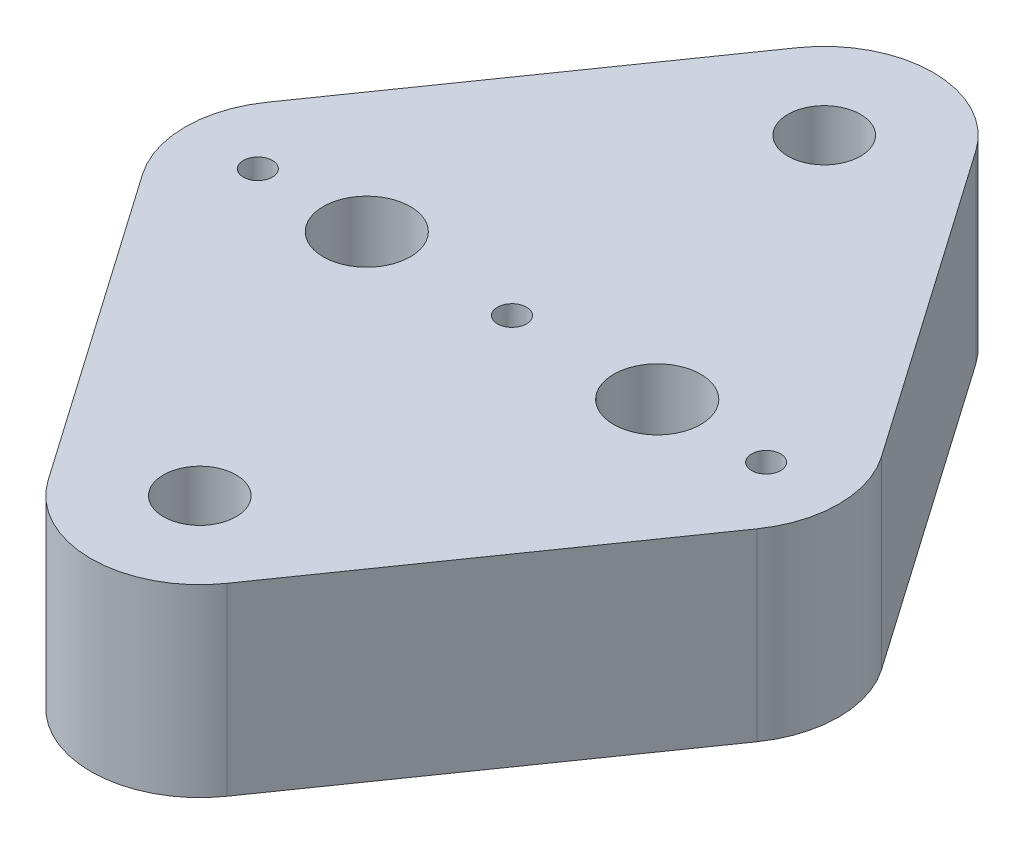
SolidWorks part; units mm, degrees
ref_plane "Front Plane" through (0, 0, 0) normal (0, 0, 1) x (1, 0, 0)
ref_plane "Top Plane" through (0, 0, 0) normal (0, 1, 0) x (1, 0, 0)
ref_plane "Right Plane" through (0, 0, 0) normal (1, 0, 0) x (0, 0, -1)
other "Default"
sketch "Sketch1" plane through (0, 0, 0) normal (0, 1, 0) x (1, 0, 0)
  line L0 (0, -21.5) -> (0, 21.5) construction
  line L1 (10, 0) -> (-10, 0) construction
  line L2 (-21.151, 4.2914) -> (-6.151, 25.7914)
  line L3 (6.151, 25.7914) -> (21.151, 4.2914)
  line L4 (21.151, -4.2914) -> (6.151, -25.7914)
  line L5 (-6.151, -25.7914) -> (-21.151, -4.2914)
  line L6 (-15, 0) -> (-10, 0) construction
  line L7 (10, 0) -> (15, 0) construction
  circle A0 centre (0, 21.5) radius 2.5
  circle A1 centre (0, -21.5) radius 2.5
  circle A3 centre (-10, 0) radius 3
  circle A4 centre (10, 0) radius 3
  arc A5 (-6.151, 25.7914) -> (6.151, 25.7914) centre (0, 21.5) cw
  arc A6 (6.151, -25.7914) -> (-6.151, -25.7914) centre (0, -21.5) cw
  arc A9 (-21.151, -4.2914) -> (-21.151, 4.2914) centre (-15, 0) cw
  arc A10 (21.151, -4.2914) -> (21.151, 4.2914) centre (15, 0) ccw
  dimension "D2" = 5
  dimension "D4" = 5
  dimension "Extrusion Holes" = 6
  dimension "D1" = 43
  dimension "D3" = 20
  dimension "Extra Wideness" = 5
extrude "Boss-Extrude1" add sketch "Sketch1" along normal mid plane 12.7
sketch "Sketch2" plane through (0, 6.35, 0) normal (0, 1, 0) x (1, 0, 0)
  line L0 (-17.5, 0) -> (17.5, 0) construction
  circle A0 centre (-17.5, 0) radius 1
  circle A1 centre (17.5, 0) radius 1
  circle A2 centre (0, 0) radius 1
  dimension "D1" = 2
  dimension "D2" = 35
extrude "Potentiometer Holes" cut sketch "Sketch2" against normal through all
